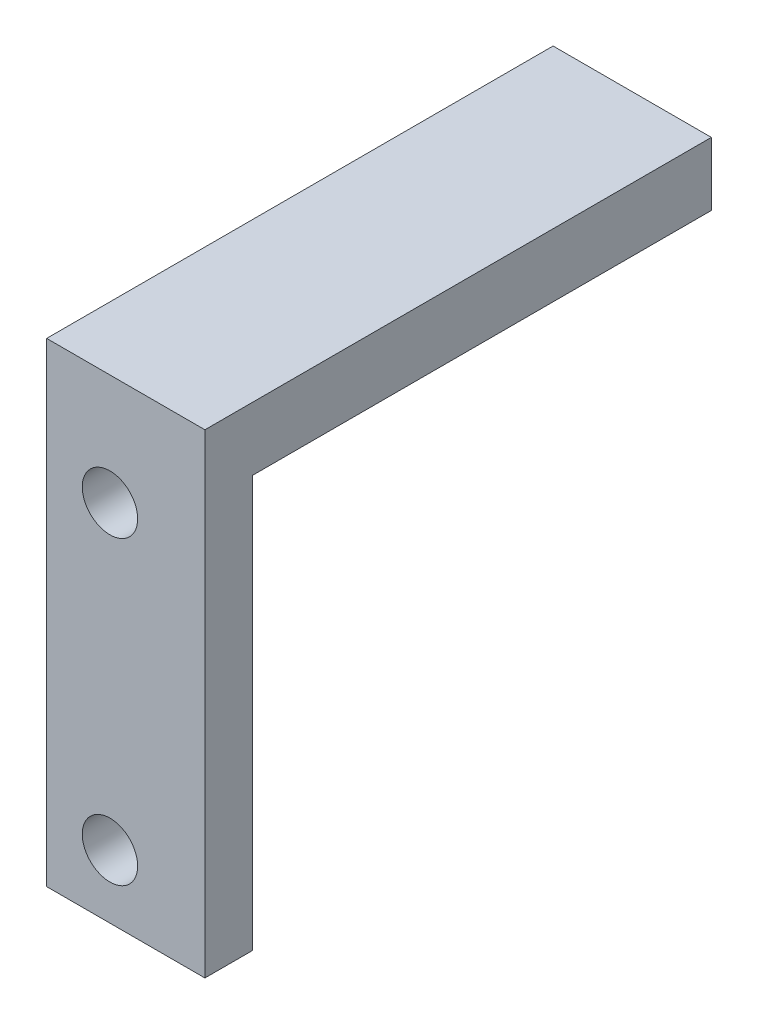
SolidWorks part; units mm, degrees
ref_plane "Front Plane" through (0, 0, 0) normal (0, 0, 1) x (1, 0, 0)
ref_plane "Top Plane" through (0, 0, 0) normal (0, 1, 0) x (1, 0, 0)
ref_plane "Right Plane" through (0, 0, 0) normal (1, 0, 0) x (0, 0, -1)
sketch "Sketch1" plane through (0, 0, 0) normal (0, 0, 1) x (1, 0, 0)
  line L0 (4, -7) -> (4, -26) construction
  line L1 (0, 0) -> (10, 0)
  line L2 (0, 0) -> (0, -30)
  line L3 (0, -30) -> (10, -30)
  line L4 (10, 0) -> (10, -30)
  circle A0 centre (4, -7) radius 1.75
  circle A1 centre (4, -26) radius 1.75
  dimension "D3" = 3.5
  dimension "D1" = 10
  dimension "D2" = 30
  dimension "D4" = 19
  dimension "D5" = 4
  dimension "D6" = 4
extrude "Boss-Extrude1" add sketch "Sketch1" along normal blind 32
sketch "Sketch2" plane through (0, 0, 0) normal (0, 0, -1) x (-1, 0, 0)
  line L0 (0, 0) -> (0, -30) construction
  line L1 (-10, -30) -> (0, -30)
  line L2 (-10, -30) -> (-10, -4)
  line L3 (-10, -4) -> (0, -4)
  line L4 (0, -30) -> (0, -4)
  line L5 (-10, 0) -> (0, 0) construction
  dimension "D1" = 4
extrude "Cut-Extrude1" cut sketch "Sketch2" against normal offset from surface (29 mm away) 3 up to face at (5.75, -7, 32)
